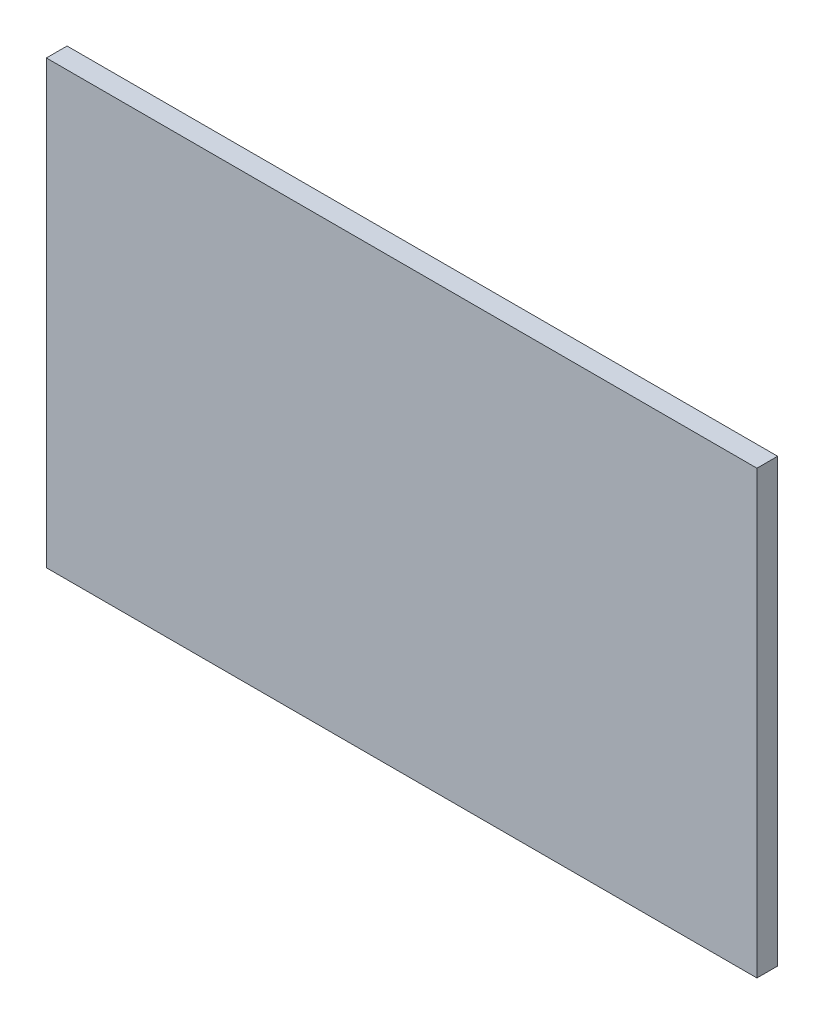
SolidWorks part; units mm, degrees
ref_plane "Płaszczyzna przednia" through (0, 0, 0) normal (0, 0, 1) x (1, 0, 0)
ref_plane "Płaszczyzna górna" through (0, 0, 0) normal (0, 1, 0) x (1, 0, 0)
ref_plane "Płaszczyzna prawa" through (0, 0, 0) normal (1, 0, 0) x (0, 0, -1)
sketch "Sketch1" plane through (0, 0, 0) normal (0, 0, 1) x (1, 0, 0)
  line L1 (51.5, -32) -> (-51.5, -32)
  line L2 (51.5, -32) -> (51.5, 32)
  line L3 (51.5, 32) -> (-51.5, 32)
  line L4 (-51.5, -32) -> (-51.5, 32)
  line L5 (51.5, -32) -> (-51.5, 32) construction
  line L6 (51.5, 32) -> (-51.5, -32) construction
  point P0 (0, 0)
  dimension "D1" = 64
  dimension "D2" = 103
extrude "Boss-Extrude1" add sketch "Sketch1" along normal blind 3
